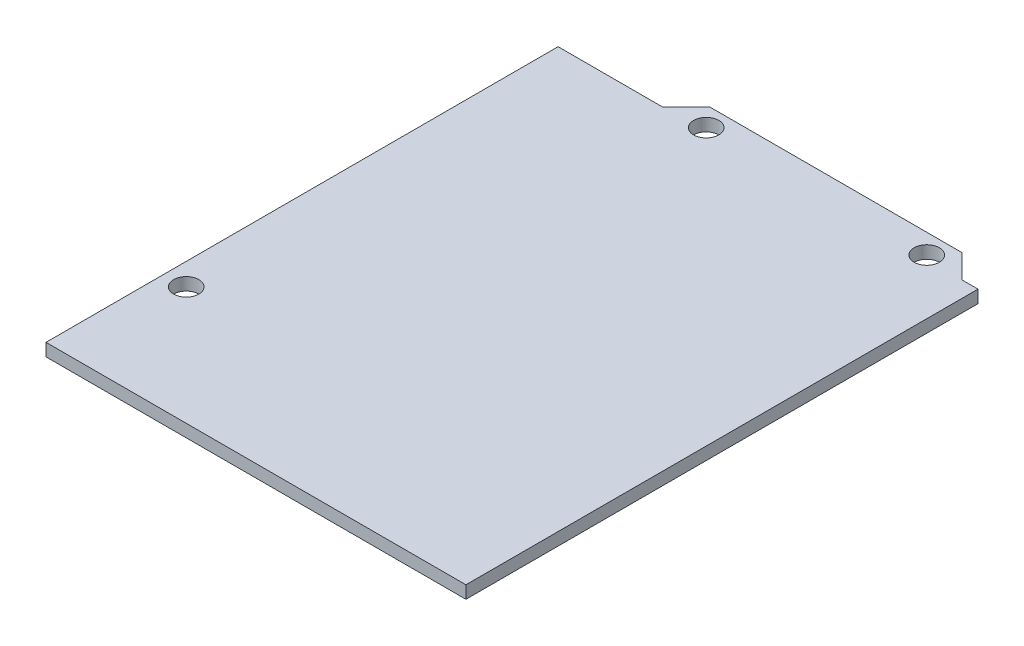
SolidWorks part; units mm, degrees
ref_plane "Front Plane" through (0, 0, 0) normal (0, 0, 1) x (1, 0, 0)
ref_plane "Top Plane" through (0, 0, 0) normal (0, 1, 0) x (1, 0, 0)
ref_plane "Right Plane" through (0, 0, 0) normal (1, 0, 0) x (0, 0, -1)
sketch "Sketch1" plane through (0, 0, 0) normal (0, 1, 0) x (1, 0, 0)
  line L0 (0, 0) -> (53.3, 0)
  line L1 (0, 0) -> (0, 65)
  line L2 (53.3, 0) -> (53.3, 65)
  line L3 (0, 65) -> (13.3, 65)
  line L4 (16.3, 68) -> (48.3, 68)
  line L5 (13.3, 65) -> (16.3, 68)
  line L6 (53.3, 65) -> (51.3, 65)
  line L7 (48.3, 68) -> (51.3, 65)
  dimension "D1" = 53.3
  dimension "D2" = 65
  dimension "D3" = 13.3
  dimension "D4" = 32
  dimension "D5" = 68
  dimension "D6" = 3
  dimension "D7" = 2
extrude "Boss-Extrude1" add sketch "Sketch1" along normal blind 1.6
sketch "Sketch2" plane through (0, 1.6, 0) normal (0, 1, 0) x (1, 0, 0)
  line L0 (53.3, 0) -> (53.3, 65) construction
  line L1 (0, 0) -> (53.3, 0) construction
  circle A0 centre (18.3, 65.5) radius 1.6
  circle A1 centre (46.3, 65.5) radius 1.6
  circle A2 centre (2.8, 15) radius 1.6
  dimension "D1" = 3.2
  dimension "D5" = 3.2
  dimension "D6" = 3.2
  dimension "D2" = 35
  dimension "D3" = 65.5
  dimension "D4" = 28
  dimension "D7" = 50.5
  dimension "D8" = 15
extrude "Cut-Extrude1" cut sketch "Sketch2" against normal blind 1.6
